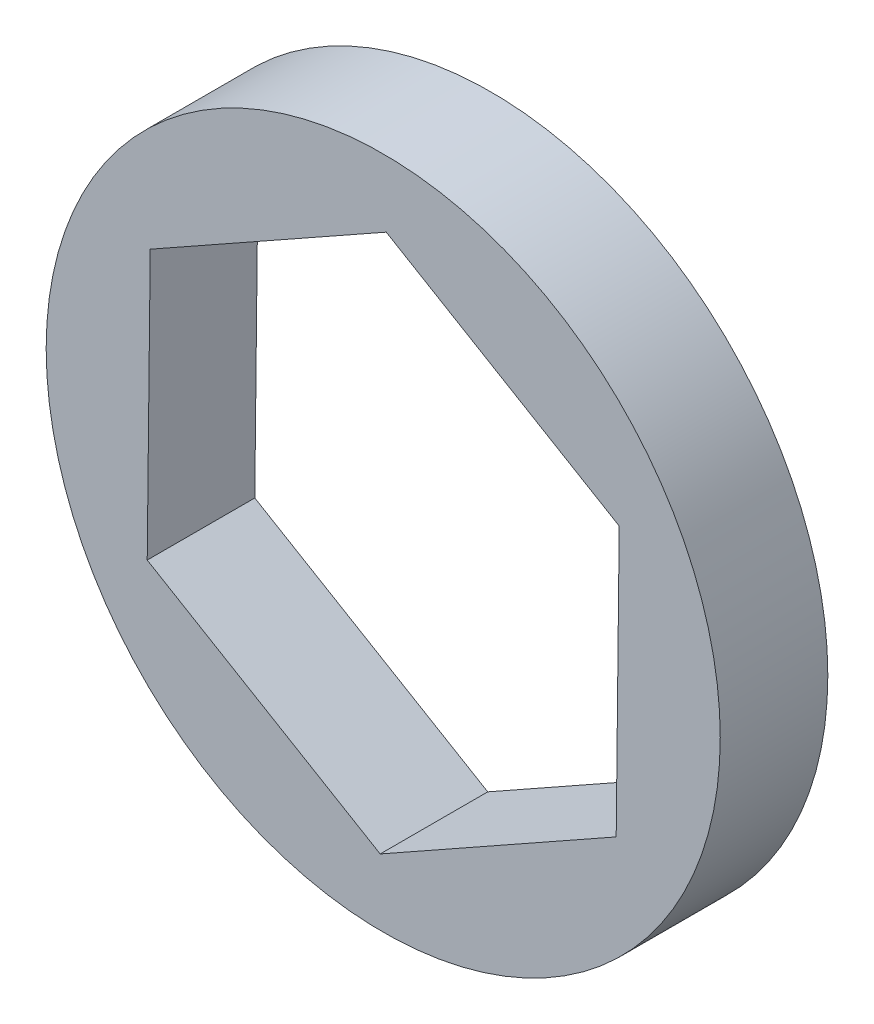
SolidWorks part; units mm, degrees
ref_plane "Alzado" through (0, 0, 0) normal (0, 0, 1) x (1, 0, 0)
ref_plane "Planta" through (0, 0, 0) normal (0, 1, 0) x (1, 0, 0)
ref_plane "Vista lateral" through (0, 0, 0) normal (1, 0, 0) x (0, 0, -1)
sketch "Croquis1" plane through (0, 0, 0) normal (0, 0, 1) x (1, 0, 0)
  line L1 (6.4973, -3.8489) -> (6.5819, 3.7023)
  line L2 (6.5819, 3.7023) -> (0.0846, 7.5513)
  line L3 (0.0846, 7.5513) -> (-6.4973, 3.8489)
  line L4 (-6.4973, 3.8489) -> (-6.5819, -3.7023)
  line L5 (-6.5819, -3.7023) -> (-0.0846, -7.5513)
  line L6 (-0.0846, -7.5513) -> (6.4973, -3.8489)
  circle A0 centre (0, 0) radius 9.4
  circle A1 centre (0, 0) radius 6.54 construction
  point P3 (6.5396, -0.0733)
  dimension "D1" = 18.8
  dimension "13.08" = 13.08
extrude "Saliente-Extruir2" add sketch "Croquis1" along normal blind 3
